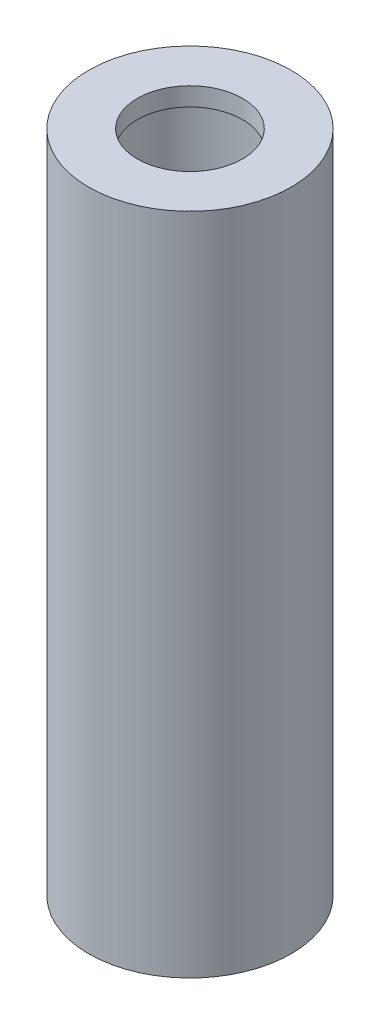
SolidWorks part; units mm, degrees
material "Brass"
ref_plane "Front Plane" through (0, 0, 0) normal (0, 0, 1) x (1, 0, 0)
ref_plane "Top Plane" through (0, 0, 0) normal (0, 1, 0) x (1, 0, 0)
ref_plane "Right Plane" through (0, 0, 0) normal (1, 0, 0) x (0, 0, -1)
sketch "Sketch1" plane through (0, 0, 0) normal (0, 1, 0) x (1, 0, 0)
  circle A0 centre (0, 0) radius 3.85
  circle A1 centre (0, 0) radius 2.6
  dimension "D1" = 7.7
  dimension "D2" = 5.2
extrude "Boss-Extrude1" add sketch "Sketch1" along normal blind 25.25
sketch "Sketch2" plane through (0, 25.25, 0) normal (0, 1, 0) x (1, 0, 0)
  circle A0 centre (0, 0) radius 3.85 construction
  circle A1 centre (0, 0) radius 3.85
  circle A2 centre (0, 0) radius 2
  dimension "D1" = 4
extrude "Boss-Extrude2" add sketch "Sketch2" against normal blind 0.7
